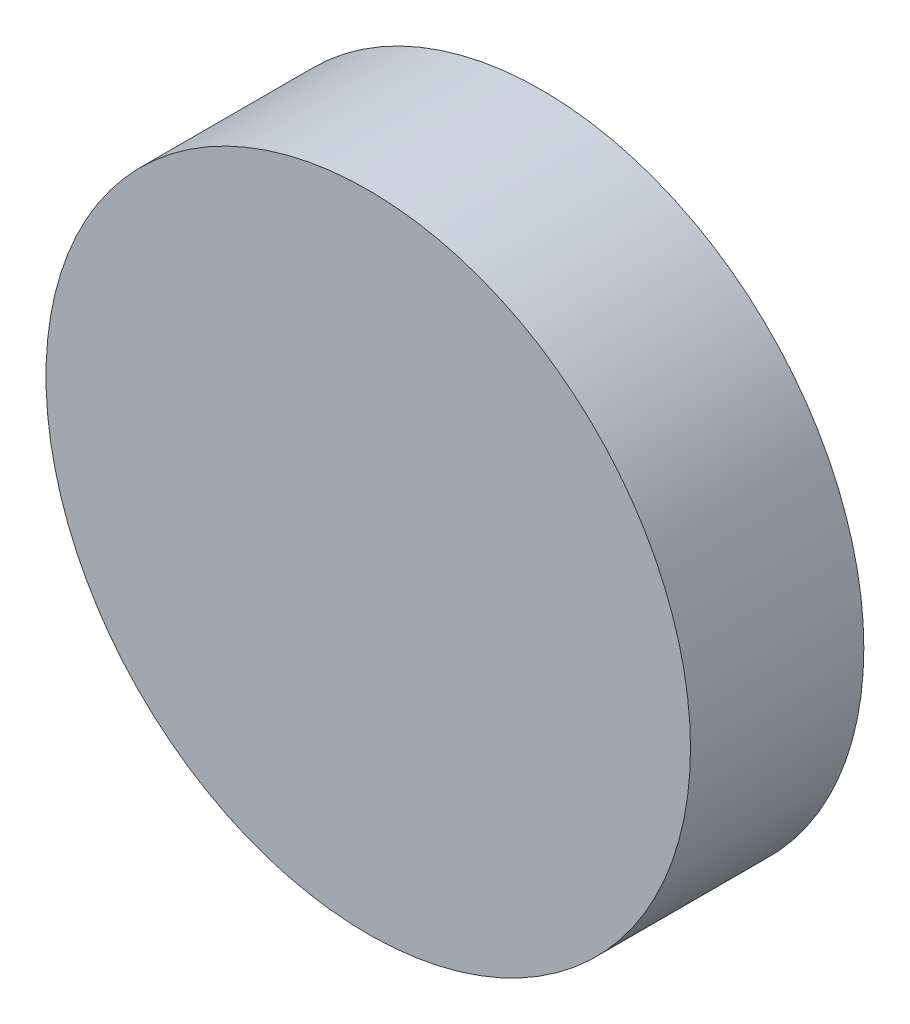
SolidWorks part; units mm, degrees
ref_plane "Ön Düzlem" through (0, 0, 0) normal (0, 0, 1) x (1, 0, 0)
ref_plane "Üst Düzlem" through (0, 0, 0) normal (0, 1, 0) x (1, 0, 0)
ref_plane "Sağ Düzlem" through (0, 0, 0) normal (1, 0, 0) x (0, 0, -1)
sketch "Çizim2" plane through (0, 0, 0) normal (0, 0, 1) x (1, 0, 0)
  circle A0 centre (-2.806, 0) radius 18.5916
extrude "Yükseklik-Ekstrüzyon1" add sketch "Çizim2" along normal blind 10
